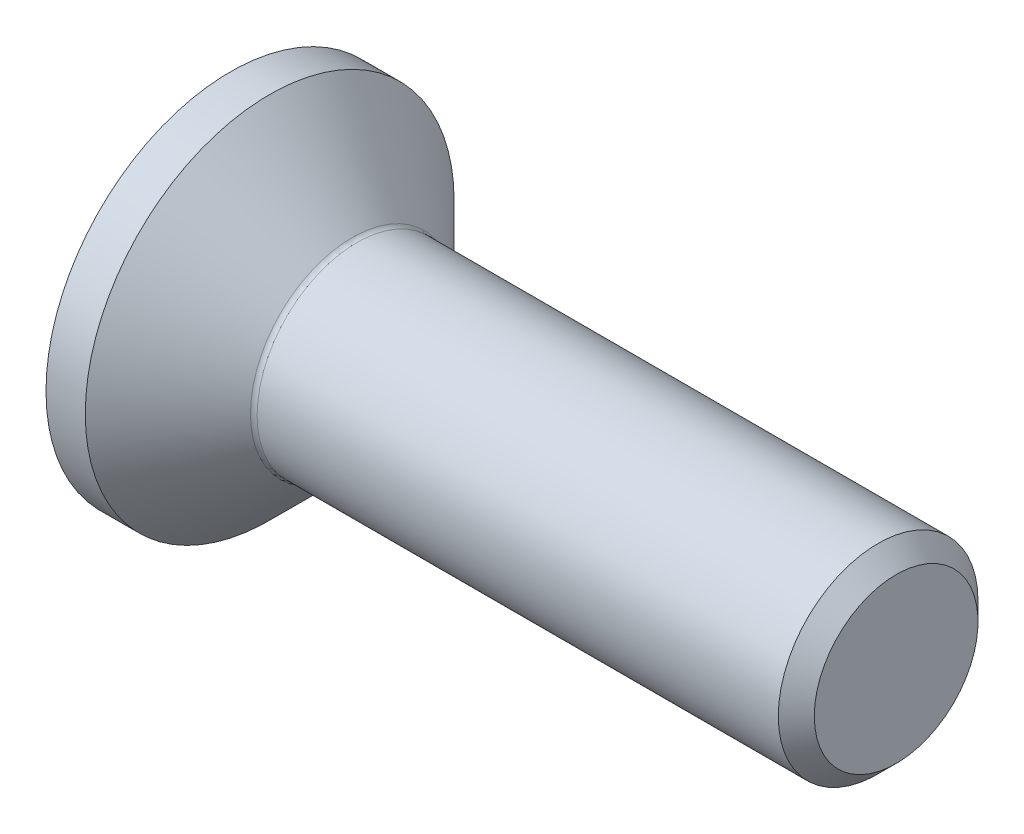
SolidWorks part; units mm, degrees
ref_plane "Front" through (0, 0, 0) normal (0, 0, 1) x (1, 0, 0)
ref_plane "Top" through (0, 0, 0) normal (0, 1, 0) x (1, 0, 0)
ref_plane "Right" through (0, 0, 0) normal (1, 0, 0) x (0, 0, -1)
sketch "Sketch1" plane through (0, 0, 0) normal (0, 0, 1) x (1, 0, 0)
  line L0 (0, 0) -> (0, 3.36)
  line L1 (0, 3.36) -> (1.86, 1.5)
  line L2 (1.86, 1.5) -> (10, 1.5)
  line L3 (10, 1.5) -> (10, 0)
  line L4 (10, 0) -> (0, 0)
  line L5 (-0.5871, 0) -> (5.4927, 0) construction
  dimension "l" = 10
  dimension "k" = 1.86
  dimension "d" = 3
  dimension "D1" = 45
revolve "Base" add sketch "Sketch1" angle 360 about L5
cosmetic thread "ThreadCosmetic1" parameters "b"=8, "D2"=2.459
sketch "Sketch2" plane through (0, 0, 0) normal (1, 0, 0) x (0, 0, -1)
  line L1 (1.1547, 0) -> (0.5774, 1)
  line L2 (0.5774, 1) -> (-0.5774, 1)
  line L3 (-0.5774, 1) -> (-1.1547, 0)
  line L4 (-1.1547, 0) -> (-0.5774, -1)
  line L5 (-0.5774, -1) -> (0.5774, -1)
  line L6 (0.5774, -1) -> (1.1547, 0)
  circle A0 centre (0, 0) radius 1 construction
  dimension "s" = 2
extrude "HexagonSocket" cut sketch "Sketch2" along normal blind 1.1
sketch "Sketch3" plane through (0, 0, 0) normal (0, 0, 1) x (1, 0, 0)
  line L0 (-0.4391, 0) -> (4.425, 0) construction
  line L1 (1.1, 0) -> (1.1, -1) construction
  line L2 (1.1, 1) -> (1.6774, 0)
  line L3 (1.6774, 0) -> (1.1, -1) construction
  line L4 (1.1, 1) -> (1.1, 0)
  line L5 (1.1, 0) -> (1.6774, 0)
  line L7 (1.1, 1) -> (1.1, 0) construction
  dimension "D1" = 120
revolve "Cut-Revolve1" cut sketch "Sketch3" angle 360 about L0
fillet "HeadFillet" radius 0.1 1 edges at (1.86, 0, 1.5)
chamfer "Chamfer" distance 0.2705 angle 45 1 edges at (10, 0, 1.5)
sketch "Sketch4" plane through (0, 0, 0) normal (0, 1, 0) x (1, 0, 0)
  line L0 (11.8531, 0) -> (-2.694, 0) construction
  line L1 (-2, 7.77) -> (3, 7.77)
  line L2 (-2, 7.77) -> (-2, 2.77)
  line L3 (-2, 2.77) -> (3, 2.77)
  line L4 (3, 7.77) -> (3, 2.77)
  line L5 (0, 3.36) -> (0, -3.36) construction
  dimension "dk" = 5.54
  dimension "D2" = 2
  dimension "D3" = 5
  dimension "D4" = 5
revolve "Cut-Revolve2" cut sketch "Sketch4" angle 360 about L0
sketch "Sketch5" plane through (0, 0, 0) normal (0, 0, 1) x (1, 0, 0)
  line L0 (9.7295, 1.2657) -> (9.8648, 1.5)
  line L1 (9.8648, 1.5) -> (9.8648, 1.7705)
  line L2 (9.8648, 1.7705) -> (9.5943, 1.7705)
  line L3 (9.5943, 1.7705) -> (9.5943, 1.5)
  line L4 (9.5943, 1.5) -> (9.7295, 1.2657)
  line L5 (0, 0) -> (10.6885, 0) construction
  line L6 (9.7295, 1.5) -> (9.7295, -1.5) construction
  dimension "D1" = 3
  dimension "D2" = 0.2705
revolve "Cut-Revolve10" [suppressed] cut sketch "Sketch5" angle 360 about L5
pattern_linear "LPattern10" [suppressed] count 25 spacing 0.3246 along (1, 0, 0)
equation "\"D1@Chamfer\" = (  \"d@Sketch1\" - \"D2@ThreadCosmetic1\" )  / 2"
equation "\"D1@Sketch5\" = \"d@Sketch1\""
equation "\"D2@Sketch5\" =  ( \"d@Sketch1\" - \"D2@ThreadCosmetic1\" )  / 2"
equation "\"D3@LPattern10\" = \"D2@Sketch5\" * 1.2"
equation "\"D1@LPattern10\" = \"b@ThreadCosmetic1\" / \"D3@LPattern10\""
